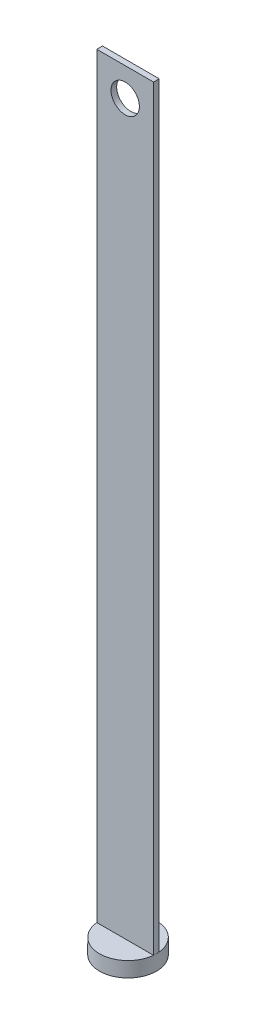
SolidWorks part; units mm, degrees
ref_plane "Płaszczyzna przednia" through (0, 0, 0) normal (0, 0, 1) x (1, 0, 0)
ref_plane "Płaszczyzna górna" through (0, 0, 0) normal (0, 1, 0) x (1, 0, 0)
ref_plane "Płaszczyzna prawa" through (0, 0, 0) normal (1, 0, 0) x (0, 0, -1)
sketch "Szkic1" plane through (0, 0, 0) normal (0, 0, 1) x (1, 0, 0)
  line L1 (-222.8136, 446.4627) -> (-192.8136, 446.4627)
  line L2 (-222.8136, 446.4627) -> (-222.8136, 46.4627)
  line L3 (-222.8136, 46.4627) -> (-192.8136, 46.4627)
  line L4 (-192.8136, 446.4627) -> (-192.8136, 46.4627)
  dimension "D1" = 30
  dimension "D2" = 400
extrude "Dodanie-wyciągnięcie1" add sketch "Szkic1" along normal blind 3
sketch "Szkic2" plane through (0, 0, 3) normal (0, 0, 1) x (1, 0, 0)
  line L0 (-192.8136, 446.4627) -> (-222.8136, 446.4627) construction
  line L1 (-222.8136, 446.4627) -> (-222.8136, 46.4627) construction
  circle A0 centre (-207.8136, 431.4627) radius 7.5
  dimension "D1" = 15
  dimension "D2" = 15
  dimension "D3" = 15
extrude "Wytnij-wyciągnięcie1" cut sketch "Szkic2" against normal blind 3 contours A0
sketch "Szkic3" plane through (0, 46.4627, 0) normal (0, -1, 0) x (1, 0, 0)
  line L0 (-222.8136, 0) -> (-192.8136, 0) construction
  circle A0 centre (-207.8136, 1.5) radius 15.0748
  dimension "D1" = 1.5
extrude "Dodanie-wyciągnięcie2" add sketch "Szkic3" along normal blind 8
